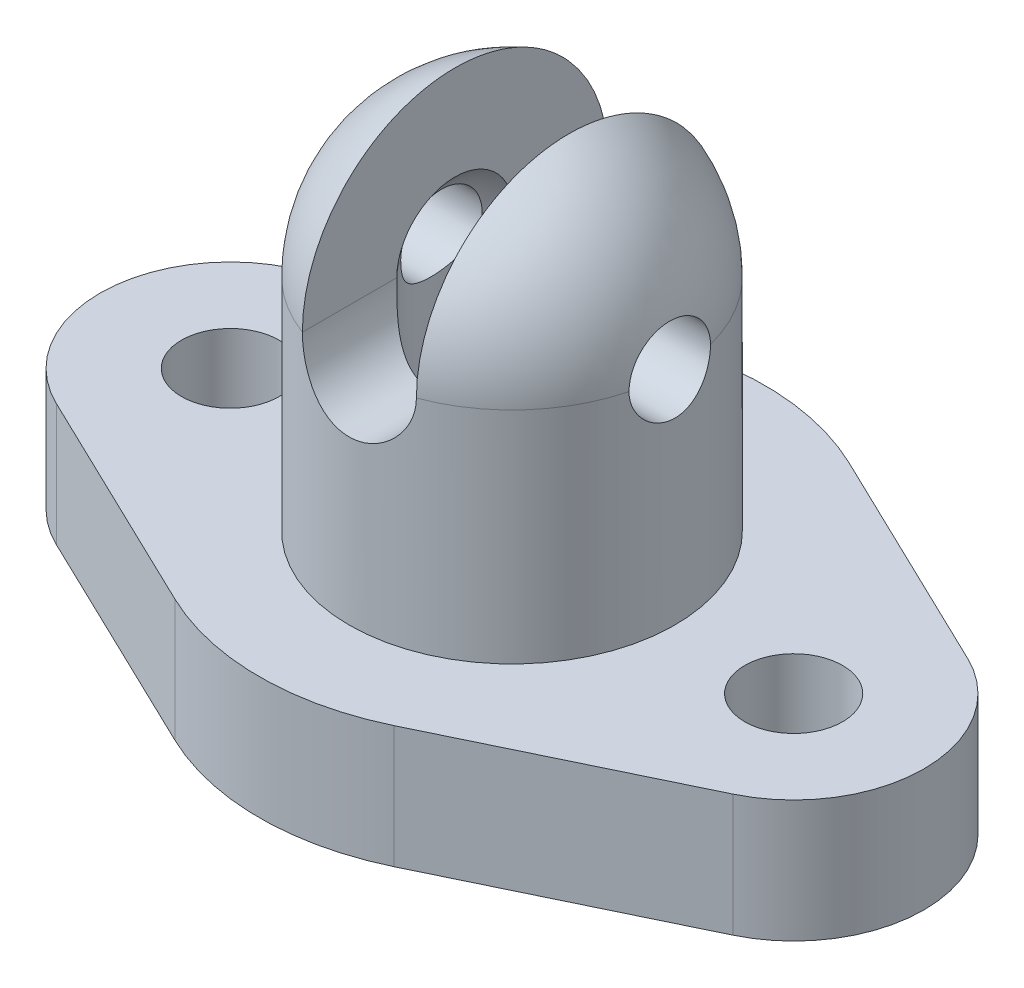
SolidWorks part; units mm, degrees
ref_plane "Front Plane" through (0, 0, 0) normal (0, 0, 1) x (1, 0, 0)
ref_plane "Top Plane" through (0, 0, 0) normal (0, 1, 0) x (1, 0, 0)
ref_plane "Right Plane" through (0, 0, 0) normal (1, 0, 0) x (0, 0, -1)
sketch "Sketch1" plane through (0, 0, 0) normal (0, 1, 0) x (1, 0, 0)
  line L0 (13.4485, -27.9309) -> (41.5174, -14.416)
  line L1 (-41.5174, -14.416) -> (-13.4485, -27.9309)
  line L2 (-41.5174, 14.416) -> (-13.4485, 27.9309)
  line L3 (41.5174, 14.416) -> (13.4485, 27.9309)
  line L4 (-50.5763, 0) -> (50.5763, 0) construction
  line L5 (0, -31) -> (0, 31) construction
  line L7 (-34.5763, 0) -> (-34.5763, 16) construction
  line L8 (-34.5763, 0) -> (-34.5763, -16) construction
  arc A0 (-41.5174, 14.416) -> (-41.5174, -14.416) centre (-34.5763, 0) ccw
  arc A1 (41.5174, -14.416) -> (41.5174, 14.416) centre (34.5763, 0) ccw
  circle A2 centre (-34.5763, 0) radius 6
  circle A3 centre (34.5763, 0) radius 6
  arc A5 (-13.4485, -27.9309) -> (13.4485, -27.9309) centre (0, 0) ccw
  arc A7 (13.4485, 27.9309) -> (-13.4485, 27.9309) centre (0, 0) ccw
  dimension "D2" = 32
  dimension "D3" = 32
  dimension "D4" = 12
  dimension "D5" = 12
  dimension "D6" = 31
  dimension "D1" = 34.5763
extrude "Boss-Extrude3" add sketch "Sketch1" along normal blind 15 contours A7 L2 A0 L1 A5 L0 A1 L3
sketch "Sketch5" plane through (0, 0, 0) normal (0, 0, 1) x (1, 0, 0)
  line L0 (0, 0) -> (0, 42)
  line L1 (-20, 42) -> (-20, 0)
  line L3 (-13.4485, 0) -> (13.4485, 0) construction
  line L4 (-20, 0) -> (0, 0)
  line L5 (0, 42) -> (0, 62)
  arc A0 (0, 62) -> (-20, 42) centre (0, 42) ccw
  dimension "D1" = 40
  dimension "D2" = 42
revolve "Revolve1" add sketch "Sketch5" angle 360 about L0
sketch "Sketch6" plane through (0, 0, 0) normal (0, 0, 1) x (1, 0, 0)
  line L0 (0, 0) -> (0, 42)
  line L1 (-13.4485, 0) -> (13.4485, 0) construction
  line L2 (-10, 42) -> (-10, 0)
  line L3 (-10, 0) -> (0, 0)
  line L4 (0, 42) -> (0, 52)
  arc A0 (0, 52) -> (-10, 42) centre (0, 42) ccw
  dimension "D1" = 20
  dimension "D2" = 42
revolve "Cut-Revolve1" cut sketch "Sketch6" angle 360 about L0
sketch "Sketch7" plane through (0, 0, 0) normal (0, 0, 1) x (1, 0, 0)
  line L0 (0, 0) -> (0, 42) construction
  line L1 (-13.4485, 0) -> (13.4485, 0) construction
  line L2 (20, 42) -> (-20, 42) construction
  line L3 (-7, 42) -> (-7, 60.735)
  line L4 (7, 42) -> (7, 60.735)
  arc A0 (-7, 42) -> (7, 42) centre (0, 42) ccw
  arc A1 (20, 42) -> (-20, 42) centre (0, 42) ccw construction
  arc A2 (7, 60.735) -> (-7, 60.735) centre (0, 42) ccw
  dimension "D1" = 14
extrude "Cut-Extrude1" cut sketch "Sketch7" against normal through all both and the other way through all
sketch "Sketch8" plane through (0, 0, 0) normal (1, 0, 0) x (0, 0, -1)
  line L0 (0, 0) -> (0, 42) construction
  line L1 (-14.416, 0) -> (14.416, 0) construction
  line L2 (18.735, 42) -> (-18.735, 42) construction
  circle A0 centre (0, 42) radius 5
  dimension "D1" = 10
extrude "Cut-Extrude2" cut sketch "Sketch8" against normal through all both and the other way through all
